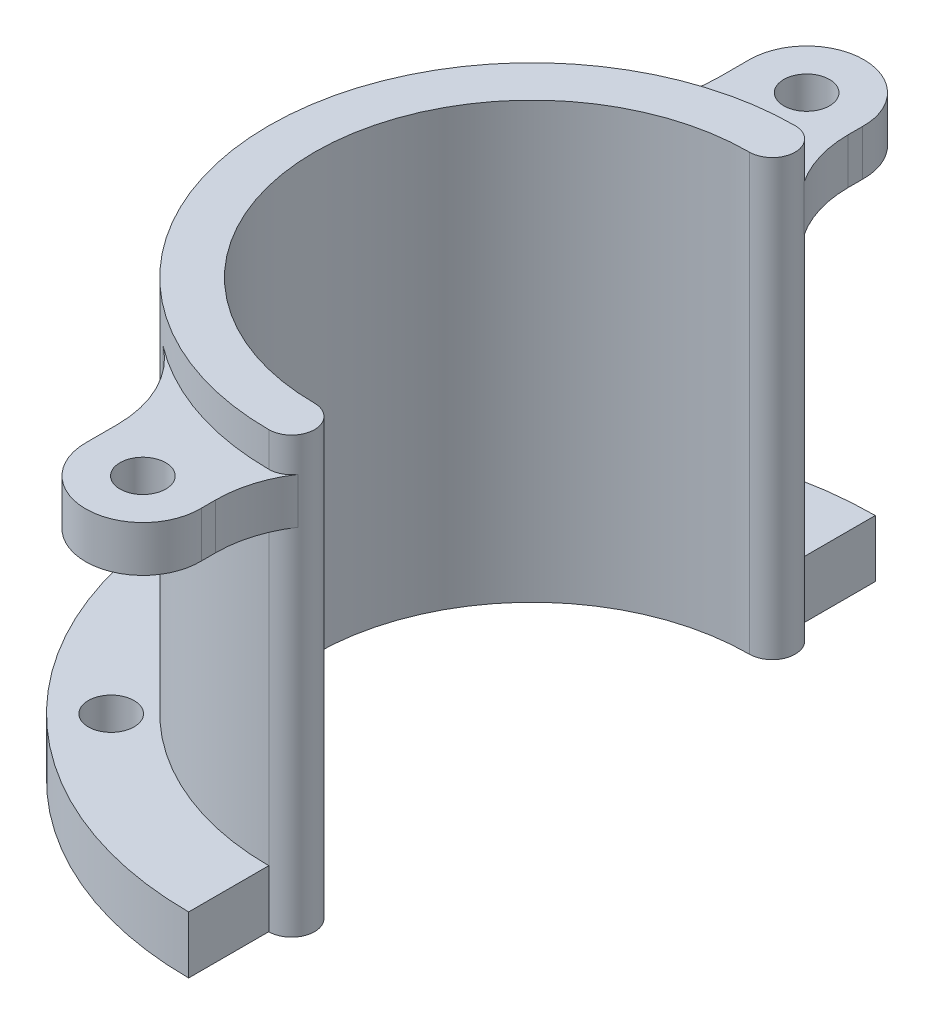
SolidWorks part; units mm, degrees
material "PET"
ref_plane "Front Plane" through (0, 0, 0) normal (0, 0, 1) x (1, 0, 0)
ref_plane "Top Plane" through (0, 0, 0) normal (0, 1, 0) x (1, 0, 0)
ref_plane "Right Plane" through (0, 0, 0) normal (1, 0, 0) x (0, 0, -1)
sketch "Sketch1" plane through (0, 0, 0) normal (0, 1, 0) x (1, 0, 0)
  line L0 (0, -44.7868) -> (0, 44.7868) construction
  arc A0 (0, -21) -> (0, 21) centre (0, 0) cw construction
  arc A1 (0, 23) -> (0, -23) centre (0, 0) ccw
  arc A2 (0, 19) -> (0, -19) centre (0, 0) ccw
  arc A3 (0, 19) -> (0, 23) centre (0, 21) ccw
  arc A4 (0, -23) -> (0, -19) centre (0, -21) ccw
  point P6 (-21, 0)
  dimension "D1" = 2
  dimension "D2" = 19
extrude "Boss-Extrude1" add sketch "Sketch1" along normal blind 38
sketch "Sketch2" plane through (0, 0, 0) normal (0, 1, 0) x (1, 0, 0)
  line L0 (0, -44.7868) -> (0, 44.7868) construction
  line L1 (0, 30) -> (0, 23)
  line L2 (0, -30) -> (0, -23)
  arc A0 (0, -30) -> (0, 30) centre (0, 0) cw
  arc A1 (0, -23) -> (0, -19) centre (0, -21) ccw construction
  arc A2 (0, 23) -> (0, -23) centre (0, 0) ccw
  arc A3 (0, 23) -> (0, -23) centre (0, 0) ccw construction
  dimension "D1" = 30
extrude "Boss-Extrude2" add sketch "Sketch2" along normal blind 5
sketch "Sketch3" plane through (0, 0, 0) normal (0, -1, 0) x (-1, 0, 0)
  line L2 (-44.2539, 0) -> (44.2539, 0) construction
  circle A0 centre (18.3848, -18.3848) radius 2
  dimension "D2" = 4
  dimension "D3" = 18.3848
  dimension "D1" = 26
extrude "Cut-Extrude1" cut sketch "Sketch3" against normal blind 5
mirror "Mirror1" about plane through (0, 0, 0) normal (0, 0, 1) of "Cut-Extrude1"
ref_plane "Plane1" through (0, 35, 0) normal (0, 1, 0) x (1, 0, 0)
sketch "Sketch4" plane through (0, 35, 0) normal (0, 1, 0) x (1, 0, 0)
  line L0 (0, -44.7868) -> (0, 44.7868) construction
  line L1 (0, 28.8779) -> (0, 23)
  line L2 (0, 23) -> (0, 30) construction
  line L3 (-9.9985, 20.713) -> (-9.9985, 29)
  arc A0 (-9.9985, 29) -> (0, 28.8779) centre (-4.9985, 29) cw
  arc A1 (0, 23) -> (-9.9985, 20.713) centre (0, 0) ccw
  arc A2 (0, 23) -> (0, -23) centre (0, 0) ccw construction
  dimension "D1" = 5
  dimension "D2" = 6
extrude "Boss-Extrude3" add sketch "Sketch4" against normal blind 4
sketch "Sketch5" plane through (0, 31, 0) normal (0, -1, 0) x (1, 0, 0)
  circle A0 centre (-4.9985, -29) radius 2
  dimension "D1" = 4
extrude "Cut-Extrude2" cut sketch "Sketch5" against normal blind 4
mirror "Mirror2" about plane through (0, 0, 0) normal (0, 0, 1) of "Cut-Extrude2", "Boss-Extrude3"
fillet "Fillet1" radius 10 4 edges at (-9.9985, 33, -20.713) (0, 33, -23) (0, 33, 23) (-9.9985, 33, 20.713)
